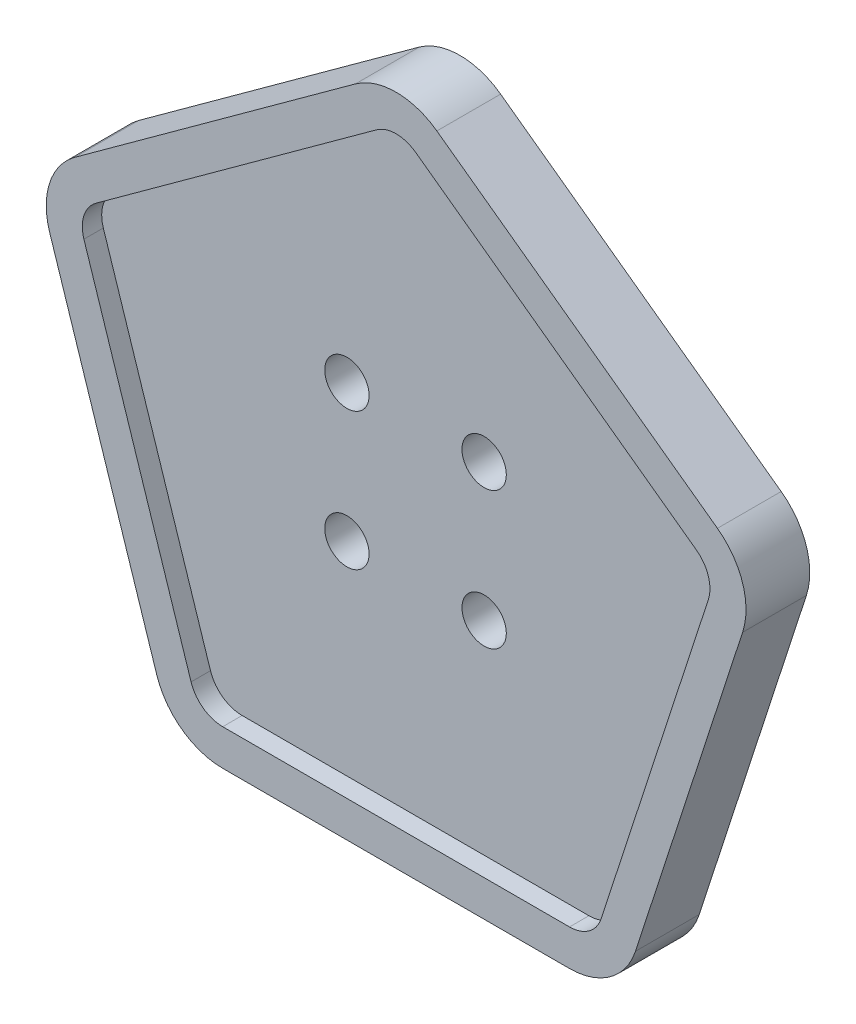
SolidWorks part; units mm, degrees
ref_plane "Front Plane" through (0, 0, 0) normal (0, 0, 1) x (1, 0, 0)
ref_plane "Top Plane" through (0, 0, 0) normal (0, 1, 0) x (1, 0, 0)
ref_plane "Right Plane" through (0, 0, 0) normal (1, 0, 0) x (0, 0, -1)
sketch "Sketch1" plane through (0, 0, 0) normal (0, 0, 1) x (1, 0, 0)
  line L1 (-4.9497, 4.9497) -> (4.9497, 4.9497) construction
  line L2 (-4.9497, 4.9497) -> (-4.9497, -4.9497) construction
  line L3 (-4.9497, -4.9497) -> (4.9497, -4.9497) construction
  line L4 (4.9497, 4.9497) -> (4.9497, -4.9497) construction
  line L5 (-4.9497, 4.9497) -> (4.9497, -4.9497) construction
  line L6 (-4.9497, -4.9497) -> (4.9497, 4.9497) construction
  line L7 (-2.9389, 25.3274) -> (-23.1796, 10.6217)
  line L8 (-24.9959, 5.0315) -> (-17.2647, -18.7628)
  line L9 (-12.5094, -22.2177) -> (12.5094, -22.2177)
  line L10 (17.2647, -18.7628) -> (24.9959, 5.0315)
  line L11 (23.1796, 10.6217) -> (2.9389, 25.3274)
  circle A1 centre (-4.9497, 4.9497) radius 1.6
  circle A2 centre (4.9497, 4.9497) radius 1.6
  circle A3 centre (4.9497, -4.9497) radius 1.6
  circle A4 centre (-4.9497, -4.9497) radius 1.6
  circle A5 centre (0, 0) radius 22.2177 construction
  arc A6 (-23.1796, 10.6217) -> (-24.9959, 5.0315) centre (-20.2406, 6.5766) ccw
  arc A7 (-17.2647, -18.7628) -> (-12.5094, -22.2177) centre (-12.5094, -17.2177) ccw
  arc A8 (12.5094, -22.2177) -> (17.2647, -18.7628) centre (12.5094, -17.2177) ccw
  arc A9 (24.9959, 5.0315) -> (23.1796, 10.6217) centre (20.2406, 6.5766) ccw
  arc A10 (-2.9389, 25.3274) -> (2.9389, 25.3274) centre (0, 21.2823) cw
  point P27 (0, 27.4626)
  point P28 (0, 26.2823)
  point P29 (0, -22.2177)
  dimension "D1" = 48.5
  dimension "D3" = 3.2
  dimension "D4" = 5
  dimension "D2" = 14
extrude "Boss-Extrude1" add sketch "Sketch1" along normal blind 4.6
sketch "Sketch3" plane through (0, 0, 4.6) normal (0, 0, 1) x (1, 0, 0)
  line L10 (-22.5232, 5.8349) -> (-14.7919, -17.9594)
  line L11 (-12.5094, -19.6177) -> (12.5094, -19.6177)
  line L12 (14.7919, -17.9594) -> (22.5232, 5.8349)
  line L13 (21.6513, 8.5182) -> (1.4107, 23.2239)
  line L14 (-1.4107, 23.2239) -> (-21.6513, 8.5182)
  line L15 (-22.5232, 5.8349) -> (-14.7919, -17.9594)
  line L16 (-12.5094, -19.6177) -> (12.5094, -19.6177)
  line L17 (14.7919, -17.9594) -> (22.5232, 5.8349)
  line L18 (21.6513, 8.5182) -> (1.4107, 23.2239)
  line L19 (-1.4107, 23.2239) -> (-21.6513, 8.5182)
  arc A10 (-21.6513, 8.5182) -> (-22.5232, 5.8349) centre (-20.2406, 6.5766) ccw
  arc A11 (-14.7919, -17.9594) -> (-12.5094, -19.6177) centre (-12.5094, -17.2177) ccw
  arc A12 (12.5094, -19.6177) -> (14.7919, -17.9594) centre (12.5094, -17.2177) ccw
  arc A13 (22.5232, 5.8349) -> (21.6513, 8.5182) centre (20.2406, 6.5766) ccw
  arc A14 (1.4107, 23.2239) -> (-1.4107, 23.2239) centre (0, 21.2823) ccw
  arc A15 (-21.6513, 8.5182) -> (-22.5232, 5.8349) centre (-20.2406, 6.5766) ccw
  arc A16 (-14.7919, -17.9594) -> (-12.5094, -19.6177) centre (-12.5094, -17.2177) ccw
  arc A17 (12.5094, -19.6177) -> (14.7919, -17.9594) centre (12.5094, -17.2177) ccw
  arc A18 (22.5232, 5.8349) -> (21.6513, 8.5182) centre (20.2406, 6.5766) ccw
  arc A19 (1.4107, 23.2239) -> (-1.4107, 23.2239) centre (0, 21.2823) ccw
  dimension "D1" = 2.6
extrude "Cut-Extrude2" cut sketch "Sketch3" against normal blind 1.4
